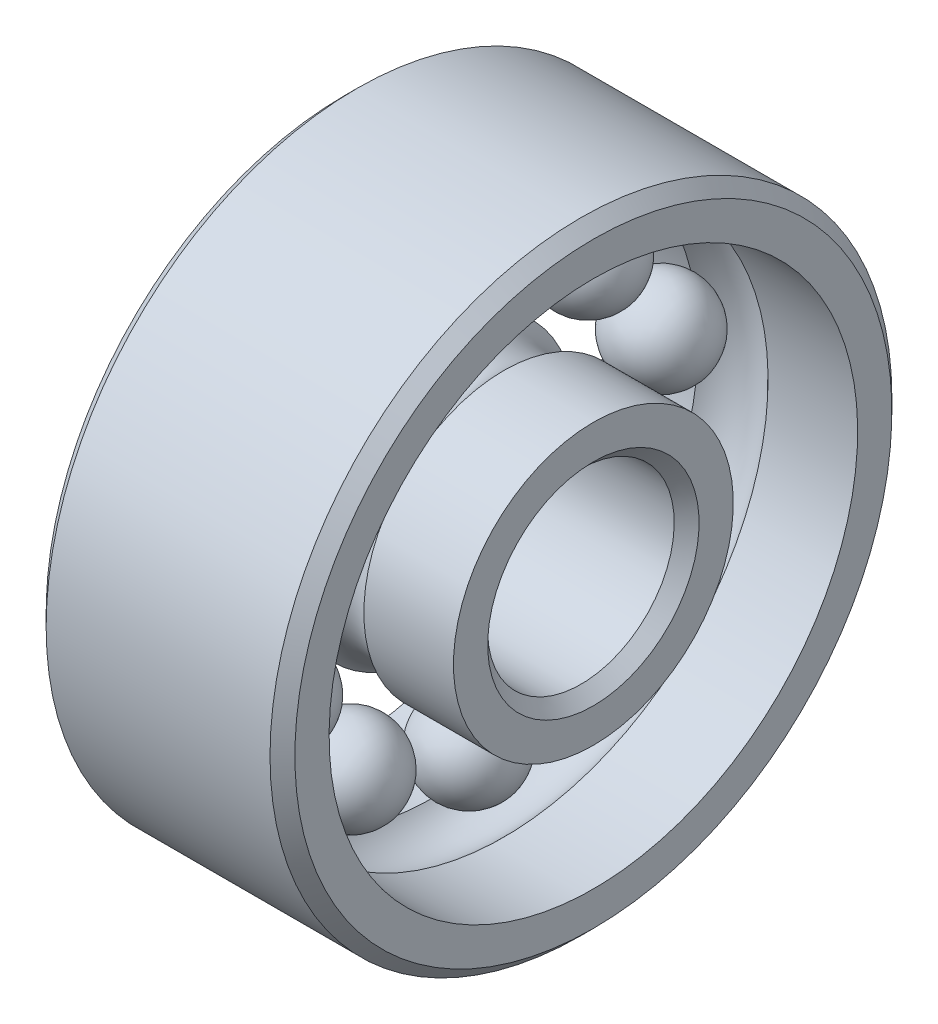
SolidWorks part; units mm, degrees
ref_plane "Front Plane" through (0, 0, 0) normal (0, 0, 1) x (1, 0, 0)
ref_plane "Top Plane" through (0, 0, 0) normal (0, 1, 0) x (1, 0, 0)
ref_plane "Right Plane" through (0, 0, 0) normal (1, 0, 0) x (0, 0, -1)
sketch "Sketch1" plane through (0, 0, 0) normal (0, 0, 1) x (1, 0, 0)
  line L0 (1.0589, 0) -> (-70.1294, 0) construction
  line L1 (2, 1.5) -> (-2, 1.5)
  line L2 (-2, 1.5) -> (-2, 2.25)
  line L3 (-2, 2.25) -> (-0.559, 2.25)
  line L4 (2, 1.5) -> (2, 2.25)
  line L5 (2, 2.25) -> (0.559, 2.25)
  line L6 (-2, 4.25) -> (-2, 5)
  line L7 (-2, 5) -> (2, 5)
  line L8 (2, 5) -> (2, 4.25)
  line L9 (2, 4.25) -> (0.559, 4.25)
  line L10 (-2, 4.25) -> (-0.559, 4.25)
  line L11 (0, 4.5) -> (0, 2) construction
  arc A0 (-0.559, 2.25) -> (0.559, 2.25) centre (0, 2.75) ccw
  arc A1 (-0.559, 4.25) -> (0.559, 4.25) centre (0, 3.75) cw
  point P6 (0, 1.5)
  point P11 (0, 2)
  dimension "D3" = 0.75
  dimension "D1" = 4
  dimension "D2" = 0.75
  dimension "D4" = 0.25
  dimension "D5" = 3
  dimension "D6" = 10
  dimension "D7" = 0.75
revolve "Revolve1" add sketch "Sketch1" angle 360 about L0
sketch "Sketch2" plane through (0, 0, 0) normal (0, 0, 1) x (1, 0, 0)
  line L0 (-0.75, 3.25) -> (0.75, 3.25)
  line L1 (0, 4.5) -> (0, 2) construction
  arc A0 (-0.75, 3.25) -> (0.75, 3.25) centre (0, 3.25) cw
  point P4 (0, 3.25)
  dimension "D1" = 1.5
revolve "Revolve2" add sketch "Sketch2" angle 360 about L0
pattern_circular "CirPattern4" count 10 over 360 about axis through (0, 0, 0) along (1, 0, 0) of bodies 103
chamfer "Chamfer1" distance 0.2 angle 45 2 edges at (-2, 5, 0) (2, 5, 0)
chamfer "Chamfer2" distance 0.2 angle 45 2 edges at (2, 1.5, 0) (-2, 1.5, 0)
equation "\"width\"=0.004000"
equation "\"OD\"=0.010000"
equation "\"ID\"=0.003000"
equation "\"race_thickness\"=0.000750"
equation "\"D_ball\"=0.001500"
equation "\"num_balls\"=10.000000"
equation "\"D1@Sketch1\"=\"width\"*1000"
equation "\"D2@Sketch1\"=\"race_thickness\"*1000"
equation "\"track_depth\"=0.000250"
equation "\"D5@Sketch1\"=\"ID\"*1000"
equation "\"D6@Sketch1\"=\"OD\"*1000"
equation "\"D7@Sketch1\"=\"race_thickness\"*1000"
equation "\"D1@CirPattern4\"=\"num_balls\""
equation "\"D3@Sketch1\"=\"D_ball\"*1000/2"
equation "\"D1@Sketch2\"=\"D_ball\"*1000"
